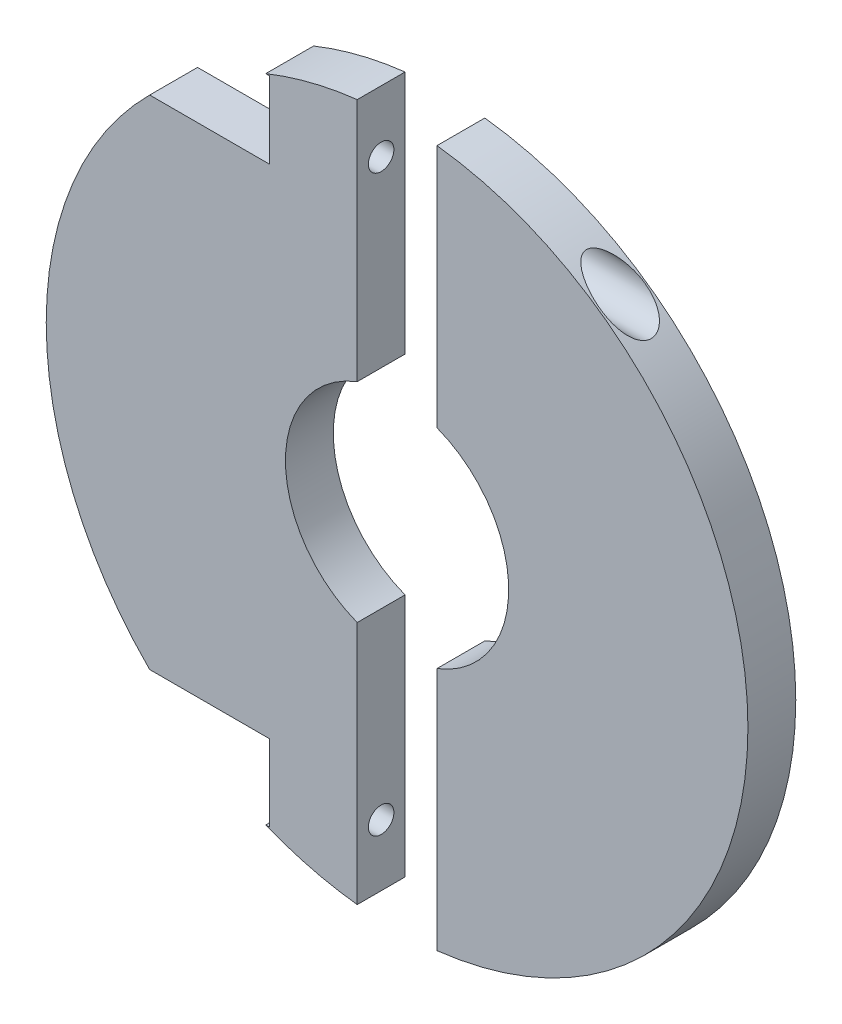
SolidWorks part; units mm, degrees
ref_plane "Front Plane" through (0, 0, 0) normal (0, 0, 1) x (1, 0, 0)
ref_plane "Top Plane" through (0, 0, 0) normal (0, 1, 0) x (1, 0, 0)
ref_plane "Right Plane" through (0, 0, 0) normal (1, 0, 0) x (0, 0, -1)
sketch "Sketch1" plane through (0, 0, 0) normal (0, 0, 1) x (1, 0, 0)
  circle A0 centre (0, 0) radius 55
  dimension "D1" = 110
extrude "Boss-Extrude1" add sketch "Sketch1" along normal blind 7.5
sketch "Sketch2" plane through (0, 0, 7.5) normal (0, 0, 1) x (1, 0, 0)
  circle A0 centre (0, 0) radius 17.5
  dimension "D1" = 35
extrude "Cut-Extrude1" cut sketch "Sketch2" against normal through all
sketch "Sketch3" plane through (0, 0, 7.5) normal (0, 0, 1) x (1, 0, 0)
  line L1 (6.25, -61.0753) -> (-6.25, -61.0753)
  line L2 (6.25, -61.0753) -> (6.25, 61.0753)
  line L3 (6.25, 61.0753) -> (-6.25, 61.0753)
  line L4 (-6.25, -61.0753) -> (-6.25, 61.0753)
  line L5 (6.25, -61.0753) -> (-6.25, 61.0753) construction
  line L6 (6.25, 61.0753) -> (-6.25, -61.0753) construction
  point P0 (0, 0)
  dimension "D1" = 12.5
extrude "Cut-Extrude2" cut sketch "Sketch3" against normal through all
sketch "Sketch4" plane through (0, 0, 0) normal (1, 0, 0) x (0, 0, -1)
  line L0 (-3.75, 54.6437) -> (-3.75, -54.6437) construction
  line L1 (0, 54.6437) -> (-7.5, 54.6437) construction
  line L2 (-7.5, -54.6437) -> (0, -54.6437) construction
  line L3 (-10.0186, 0) -> (5.0382, 0) construction
  line L4 (-97.2433, 0) -> (24.5351, 0) construction
  circle A0 centre (-3.75, 45) radius 2
  circle A1 centre (-3.75, -45) radius 2
  dimension "D1" = 4
  dimension "D2" = 45
extrude "Cut-Extrude3" cut sketch "Sketch4" against normal through all both and the other way through all
sketch "Sketch5" plane through (0, 0, 0) normal (1, 0, 0) x (0, 0, -1)
  line L0 (-11.6912, 0) -> (7.4415, 0) construction
  circle A0 centre (-3.75, 45) radius 3.5
  circle A1 centre (-3.75, -45) radius 3.5
  dimension "D1" = 7
extrude "Cut-Extrude5" cut sketch "Sketch5" against normal blind 20 from offset 40
sketch "Sketch6" plane through (0, 0, 0) normal (1, 0, 0) x (0, 0, -1)
  line L0 (-7.5, 54.6437) -> (-7.5, -54.6437) construction
  line L1 (0, 39) -> (-7.5, 39)
  line L2 (0, 39) -> (0, 51)
  line L3 (0, 51) -> (-7.5, 51)
  line L4 (-7.5, 39) -> (-7.5, 51)
  line L5 (0, 39) -> (-7.5, 51) construction
  line L6 (0, 51) -> (-7.5, 39) construction
  line L7 (-12.5276, 0) -> (14.5509, 0) construction
  line L8 (0, -39) -> (0, -51)
  line L9 (0, -39) -> (-7.5, -39)
  line L10 (-7.5, -39) -> (-7.5, -51)
  line L11 (0, -51) -> (-7.5, -51)
  point P0 (-3.75, 45)
  dimension "D1" = 12
extrude "Cut-Extrude6" cut sketch "Sketch6" against normal blind 20 from offset 20 offset against normal yes
